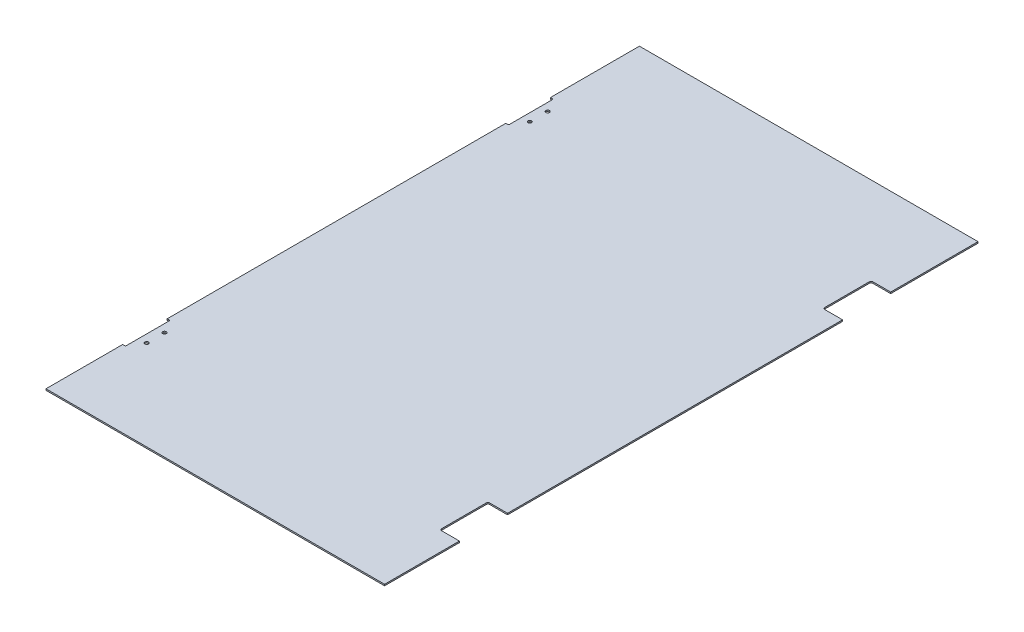
SolidWorks part; units mm, degrees
ref_plane "Front Plane" through (0, 0, 0) normal (0, 0, 1) x (1, 0, 0)
ref_plane "Top Plane" through (0, 0, 0) normal (0, 1, 0) x (1, 0, 0)
ref_plane "Right Plane" through (0, 0, 0) normal (1, 0, 0) x (0, 0, -1)
sketch "Sketch1" plane through (0, 0, 0) normal (0, 1, 0) x (1, 0, 0)
  line L0 (65.3263, 149.0698) -> (95.3263, 149.0698)
  line L1 (-94.6737, 149.0698) -> (-64.6737, 149.0698)
  line L2 (-94.6737, 149.0698) -> (-94.6737, -183.9302)
  line L3 (-94.6737, -183.9302) -> (95.3263, -183.9302)
  line L4 (95.3263, 149.0698) -> (95.3263, -183.9302)
  line L13 (-39.6737, 149.0698) -> (40.3263, 149.0698)
  line L14 (-64.6737, 149.0698) -> (-39.6737, 149.0698)
  line L15 (65.3263, 149.0698) -> (40.3263, 149.0698)
  point P4 (-64.6737, 149.0698)
  point P5 (-94.6737, 149.0698)
  point P15 (65.3263, 149.0698)
  point P16 (40.3263, 149.0698)
  dimension "D1" = 333
  dimension "D2" = 190
  dimension "D6" = 30
extrude "Panel" add sketch "Sketch1" along normal blind 0.79
ref_plane "Length" through (0.3263, 0, 0) normal (-1, 0, 0) x (0, 0, 1)
ref_plane "Width" through (0, 0, 20.9302) normal (0, 0, -1) x (-1, 0, 0)
sketch "Text" plane through (0, 0, 0) normal (0, -1, 0) x (1, 0, 0)
  text T0 "Inner Side Panel, \r\nReflectarray\r\n" font "Century Gothic" height 10
sketch "Sketch5" plane through (0, 0, 0) normal (0, -1, 0) x (1, 0, 0)
  line L0 (-94.6737, -149.0698) -> (-94.6737, 183.9302) construction
  line L1 (95.3263, -149.0698) -> (-94.6737, -149.0698) construction
  line L3 (-94.6737, -99.0698) -> (-93.5937, -99.0698)
  line L4 (-94.6737, -99.0698) -> (-94.6737, -74.0698)
  line L5 (-94.6737, -74.0698) -> (-93.5937, -74.0698)
  line L6 (-93.0937, -98.5698) -> (-93.0937, -74.5698)
  line L7 (-94.6737, -94.0698) -> (-84.6737, -94.0698) construction
  line L8 (-94.6737, -94.0698) -> (-94.6737, -79.0698) construction
  line L9 (-94.6737, -79.0698) -> (-84.6737, -79.0698) construction
  line L10 (-84.6737, -94.0698) -> (-84.6737, -79.0698) construction
  arc A0 (-93.0937, -98.5698) -> (-93.5937, -99.0698) centre (-93.5937, -98.5698) cw
  arc A1 (-93.0937, -74.5698) -> (-93.5937, -74.0698) centre (-93.5937, -74.5698) ccw
  circle A2 centre (-88.6737, -91.5698) radius 1
  circle A3 centre (-88.6737, -81.5698) radius 1
  point P0 (-94.6737, -99.0698)
  point P15 (-93.0937, -99.0698)
  point P18 (-93.0937, -74.0698)
  point P19 (-88.6737, -81.5698)
  point P20 (-88.6737, -91.5698)
  dimension "D6" = 0.5
  dimension "D7" = 0.5
  dimension "D13" = 2
  dimension "D14" = 2
  dimension "D1" = 50
  dimension "D2" = 25
  dimension "D3" = 1.58
  dimension "D4" = 5
  dimension "D5" = 15
  dimension "D8" = 10
  dimension "D9" = 2.5
  dimension "D10" = 4
  dimension "D11" = 2.5
  dimension "D12" = 4
extrude "Hinge Mount" cut sketch "Sketch5" against normal blind 10
sketch "Sketch6" plane through (0, 0, 0) normal (0, -1, 0) x (1, 0, 0)
  line L6 (95.3263, 183.9302) -> (95.3263, -149.0698) construction
  line L7 (95.3263, -100.0698) -> (85.3263, -100.0698)
  line L8 (95.3263, -100.0698) -> (95.3263, -73.0698)
  line L9 (95.3263, -73.0698) -> (85.3263, -73.0698)
  line L10 (84.3263, -99.0698) -> (84.3263, -74.0698)
  line L11 (95.3263, -149.0698) -> (-94.6737, -149.0698) construction
  arc A2 (85.3263, -73.0698) -> (84.3263, -74.0698) centre (85.3263, -74.0698) ccw
  arc A3 (84.3263, -99.0698) -> (85.3263, -100.0698) centre (85.3263, -99.0698) ccw
  dimension "D4" = 1
  dimension "D1" = 49
  dimension "D2" = 27
  dimension "D3" = 11
extrude "Hinge Cutout" cut sketch "Sketch6" against normal blind 10
mirror "Mirror1" about plane through (0, 0, 20.9302) normal (0, 0, -1) of "Hinge Cutout", "Hinge Mount"
